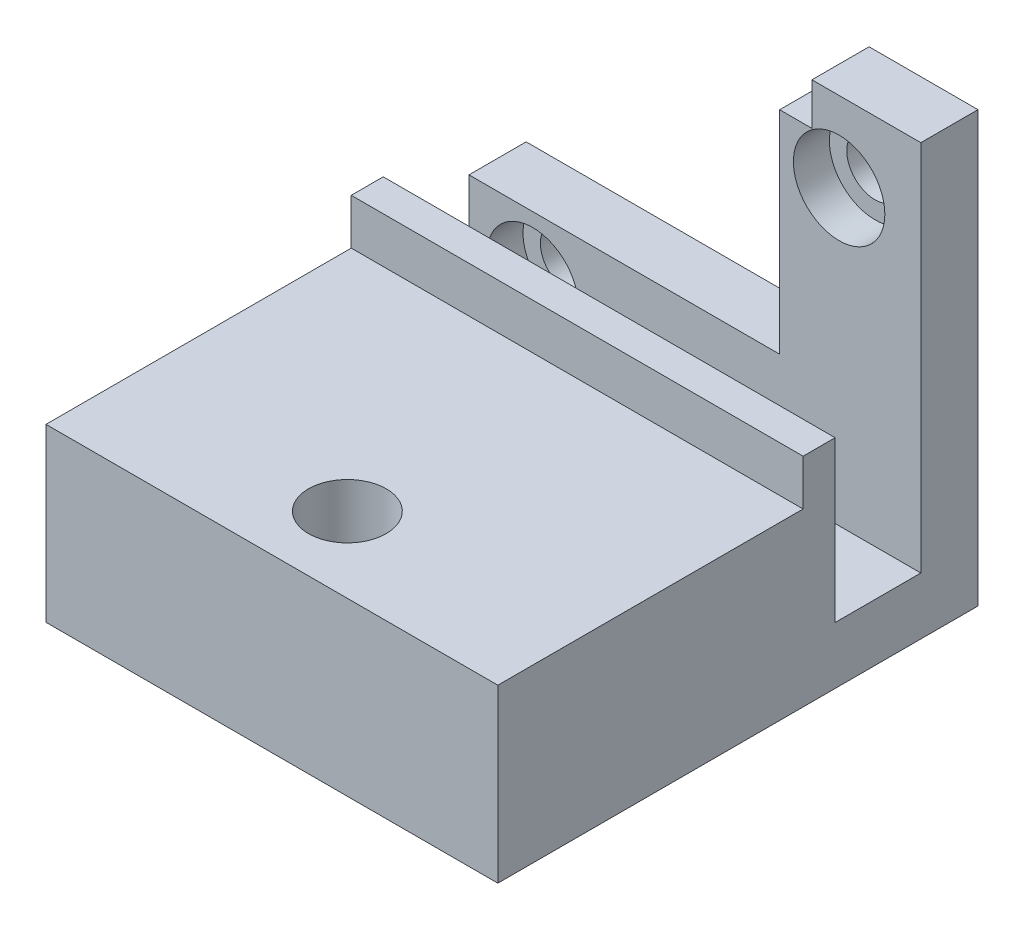
SolidWorks part; units mm, degrees
ref_plane "Front Plane" through (0, 0, 0) normal (0, 0, 1) x (1, 0, 0)
ref_plane "Top Plane" through (0, 0, 0) normal (0, 1, 0) x (1, 0, 0)
ref_plane "Right Plane" through (0, 0, 0) normal (1, 0, 0) x (0, 0, -1)
sketch "Sketch2" plane through (0, 0, 0) normal (0, 0, 1) x (1, 0, 0)
  line L0 (4.3952, 7.8274) -> (4.3952, -1.4384)
  line L1 (4.3952, -1.4384) -> (-11.8608, -1.4384)
  line L2 (-11.8608, -1.4384) -> (-11.8608, -8.0424)
  line L3 (-11.8608, -8.0424) -> (12.2372, -8.0424)
  line L4 (12.2372, -8.0424) -> (12.2372, 12.6586)
  line L5 (12.2372, 12.6586) -> (7.6972, 12.6586)
  line L7 (7.6972, 12.6586) -> (6.1882, 12.6586)
  line L8 (-11.8608, -1.4384) -> (-12.8608, -1.4384)
  line L9 (-11.8608, -1.4384) -> (-11.8608, -8.0424)
  line L10 (-11.8608, -8.0424) -> (-12.8608, -8.0424)
  line L11 (-12.8608, -1.4384) -> (-12.8608, -8.0424)
  line L12 (4.3952, 10.3218) -> (4.3952, 7.8274)
  line L13 (4.3952, 10.3218) -> (6.1882, 10.3218)
  line L14 (6.1882, 10.3218) -> (6.1882, 12.6586)
  circle A0 centre (7.6972, 8.2136) radius 1.5748
  circle A1 centre (-9.3208, -4.7404) radius 1.5748
  point P0 (6.4597, 9.1875)
  dimension "D5" = 4.445
  dimension "D7" = 3.1496
  dimension "D9" = 3.1496
  dimension "D1" = 1
  dimension "D2" = 3.302
  dimension "D3" = 3.302
  dimension "D4" = 24.098
  dimension "D6" = 2.54
  dimension "D8" = 17.018
  dimension "D10" = 14.097
extrude "Boss-Extrude1" add sketch "Sketch2" along normal blind 3.175 contours A0 | L8 L11 L10 L2 | A1
sketch "Sketch3" plane through (0, 0, 0) normal (0, 0, -1) x (-1, 0, 0)
  line L6 (-12.2372, -8.0424) -> (12.8608, -8.0424)
  line L7 (-12.2372, -8.0424) -> (-12.2372, -11.2174)
  line L8 (-12.2372, -11.2174) -> (12.8608, -11.2174)
  line L9 (12.8608, -8.0424) -> (12.8608, -11.2174)
  dimension "D1" = 3.175
extrude "Boss-Extrude3" add sketch "Sketch3" against normal blind 26.67
sketch "Sketch4" plane through (0, -11.2174, 0) normal (0, -1, 0) x (1, 0, 0)
  line L1 (-0.3118, 26.67) -> (-0.3118, 3.0754) construction
  line L2 (12.2372, 26.67) -> (-12.8608, 26.67) construction
  circle A0 centre (-0.3118, 22.479) radius 2.159
  dimension "D1" = 4.318
  dimension "D2" = 4.191
sketch "Sketch5" plane through (0, 0, 3.175) normal (0, 0, 1) x (1, 0, 0)
  circle A0 centre (7.6972, 8.2136) radius 2.54
  circle A1 centre (-9.3208, -4.7404) radius 2.54
  dimension "D1" = 5.08
  dimension "D2" = 5.08
extrude "Cut-Extrude2" cut sketch "Sketch5" against normal blind 2
sketch "Sketch6" plane through (0, -8.0424, 0) normal (0, 1, 0) x (1, 0, 0)
  line L0 (12.2372, -26.67) -> (12.2372, -3.175) construction
  line L1 (-12.8608, -26.67) -> (12.2372, -26.67)
  line L2 (-12.8608, -26.67) -> (-12.8608, -7.9375)
  line L3 (-12.8608, -7.9375) -> (12.2372, -7.9375)
  line L4 (12.2372, -26.67) -> (12.2372, -7.9375)
  dimension "D1" = 18.7325
extrude "Boss-Extrude4" add sketch "Sketch6" along normal blind 6.35
extrude "Cut-Extrude3" cut sketch "Sketch4" against normal through all
sketch "Sketch7" plane through (0, -1.6924, 0) normal (0, 1, 0) x (1, 0, 0)
  line L0 (12.2372, -26.67) -> (12.2372, -7.9375) construction
  line L1 (-12.8608, -7.9375) -> (12.2372, -7.9375)
  line L2 (-12.8608, -7.9375) -> (-12.8608, -9.7155)
  line L3 (-12.8608, -9.7155) -> (12.2372, -9.7155)
  line L4 (12.2372, -7.9375) -> (12.2372, -9.7155)
  dimension "D1" = 1.778
extrude "Boss-Extrude5" add sketch "Sketch7" along normal blind 2.54
